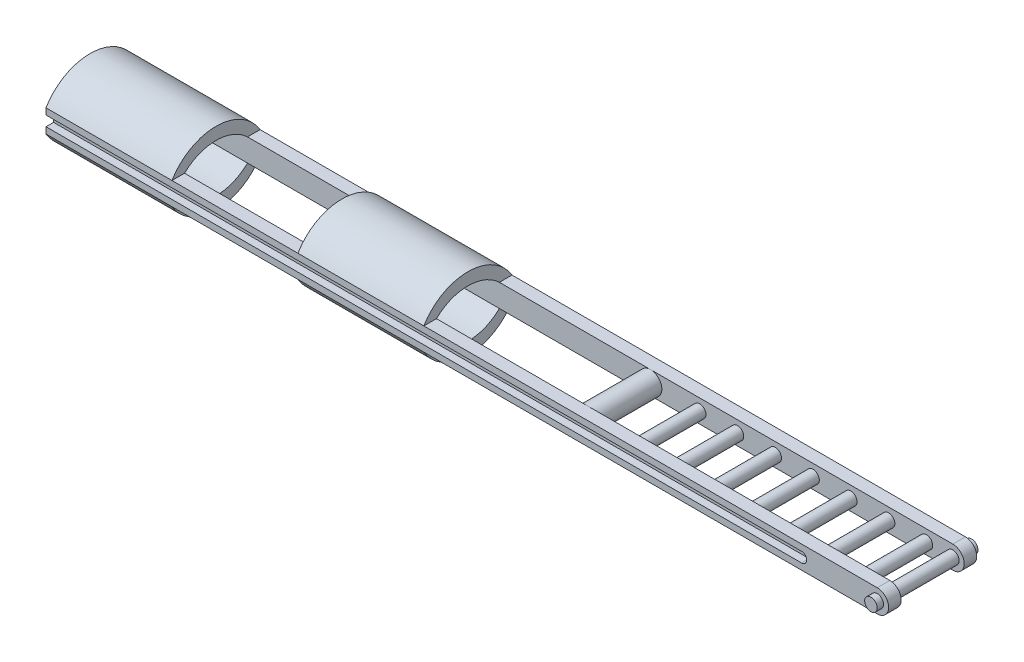
SolidWorks part; units mm, degrees
material "6061-T6 (SS)"
ref_plane "Front" through (0, 0, 0) normal (0, 0, 1) x (1, 0, 0)
ref_plane "Top" through (0, 0, 0) normal (0, 1, 0) x (1, 0, 0)
ref_plane "Right" through (0, 0, 0) normal (1, 0, 0) x (0, 0, -1)
sketch "Croquis1" plane through (0, 0, 0) normal (0, 0, 1) x (1, 0, 0)
  circle A0 centre (0, 0) radius 4.5
  dimension "D1" = 9
extrude "Saliente-Extruir1" add sketch "Croquis1" along normal mid plane 25
sketch "Croquis2" plane through (0, 0, 12.5) normal (0, 0, 1) x (1, 0, 0)
  line L0 (0, 4.5) -> (120, 4.5)
  line L1 (0, -4.5) -> (120, -4.5)
  line L2 (0, 0) -> (120, 0) construction
  arc A0 (120, -4.5) -> (120, 4.5) centre (120, 0) ccw
  circle A1 centre (0, 0) radius 4.5
  arc A2 (0, 4.5) -> (0, -4.5) centre (0, 0) ccw
  dimension "D2" = 120
  dimension "D1" = 0
extrude "Saliente-Extruir2" add sketch "Croquis2" along normal blind 5
mirror "Simetría1" about plane through (0, 0, 0) normal (0, 0, 1) of "Saliente-Extruir2"
sketch "Croquis4" plane through (0, 0, 0) normal (0, 0, 1) x (1, 0, 0)
  circle A0 centre (120, 0) radius 2.5
  arc A2 (120, -4.5) -> (120, 4.5) centre (120, 0) ccw construction
  dimension "D1" = 5
extrude "Saliente-Extruir3" add sketch "Croquis4" along normal mid plane 40
sketch "Croquis5" plane through (0, 0, 17.5) normal (0, 0, 1) x (1, 0, 0)
  line L0 (0, 2) -> (90, 2)
  line L2 (90, -2) -> (0, -2)
  arc A0 (0, 2) -> (0, -2) centre (0, 0) ccw
  arc A1 (90, -2) -> (90, 2) centre (90, 0) ccw
  dimension "D1" = 4
  dimension "D2" = 90
extrude "Cortar-Extruir1" cut sketch "Croquis5" against normal blind 3
mirror "Simetría2" about plane through (0, 0, 0) normal (0, 0, 1) of "Cortar-Extruir1"
sketch "Croquis6" plane through (0, 0, -17.5) normal (0, 0, -1) x (-1, 0, 0)
  line L0 (0, 4.5) -> (210, 4.5)
  line L1 (210, 4.5) -> (210, -4.5)
  line L2 (210, -4.5) -> (0, -4.5)
  arc A0 (0, -4.5) -> (0, 4.5) centre (0, 0) ccw construction
  arc A1 (0, -4.5) -> (0, 4.5) centre (0, 0) ccw
  dimension "D1" = 210
extrude "Saliente-Extruir4" add sketch "Croquis6" against normal up to surface (5 mm away) up to face at (117.5, 0, -12.5)
sketch "Croquis7" plane through (0, 0, -14.5) normal (0, 0, -1) x (-1, 0, 0)
  line L0 (0, 2) -> (256.9255, 2)
  line L1 (256.9255, 2) -> (256.9255, -2)
  line L2 (256.9255, -2) -> (0, -2)
  line L3 (0, 2) -> (0, -2)
extrude "Cortar-Extruir2" cut sketch "Croquis7" along normal blind 10
sketch "Croquis8" plane through (0, 0, 17.5) normal (0, 0, 1) x (1, 0, 0)
  line L0 (0, 4.5) -> (-210, 4.5)
  line L1 (-210, 4.5) -> (-210, -4.5)
  line L2 (-210, -4.5) -> (0, -4.5)
  arc A1 (0, 4.5) -> (0, -4.5) centre (0, 0) ccw construction
  arc A2 (0, 4.5) -> (0, -4.5) centre (0, 0) ccw
extrude "Saliente-Extruir6" add sketch "Croquis8" against normal up to surface (5 mm away) up to face at (122.5, 0, 12.5)
sketch "Croquis9" plane through (0, 0, 14.5) normal (0, 0, 1) x (1, 0, 0)
  line L0 (0, 2) -> (-256.9979, 2)
  line L1 (-256.9979, 2) -> (-256.9979, -2)
  line L2 (-256.9979, -2) -> (0, -2)
  line L3 (0, -2) -> (90, -2) construction
  line L4 (0, -2) -> (0, 2)
  arc A0 (0, 2) -> (0, -2) centre (0, 0) ccw construction
extrude "Cortar-Extruir3" cut sketch "Croquis9" along normal blind 10
sketch "Croquis10" plane through (0, 0, -12.5) normal (0, 0, 1) x (1, 0, 0)
  line L0 (124.5, 0) -> (0, 0) construction
  circle A0 centre (109.5, 0) radius 2.5
  circle A1 centre (120, 0) radius 2.5 construction
  arc A2 (120, -4.5) -> (120, 4.5) centre (120, 0) ccw construction
  circle A3 centre (94.5, 0) radius 2.5
  circle A4 centre (79.5, 0) radius 2.5
  circle A5 centre (64.5, 0) radius 2.5
  circle A6 centre (49.5, 0) radius 2.5
  circle A7 centre (34.5, 0) radius 2.5
  circle A8 centre (19.5, 0) radius 2.5
  dimension "D1" = 15
  dimension "D2" = 7
extrude "Saliente-Extruir7" add sketch "Croquis10" along normal up to surface (25 mm away) up to face at (122.5, 0, 12.5)
sketch "Croquis13" plane through (-210, 0, 0) normal (-1, 0, 0) x (0, 0, 1)
  line L8 (-14.5, 2) -> (-14.5, -2)
  line L9 (-14.5, -2) -> (-17.5, -2)
  line L10 (-17.5, -2) -> (-17.5, -4.5)
  line L11 (-17.5, -4.5) -> (-12.5, -4.5)
  line L12 (-12.5, -4.5) -> (-12.5, 4.5)
  line L13 (-12.5, 4.5) -> (-17.5, 4.5)
  line L14 (-17.5, 4.5) -> (-17.5, 2)
  line L15 (-17.5, 2) -> (-14.5, 2)
  line L18 (-17.5, -2) -> (-17.5, -4.5)
  line L21 (-12.5, 4.5) -> (-17.5, 4.5)
  line L24 (14.5, -2) -> (14.5, 2)
  line L25 (14.5, 2) -> (17.5, 2)
  line L26 (17.5, 2) -> (17.5, 4.5)
  line L27 (17.5, 4.5) -> (12.5, 4.5)
  line L28 (12.5, 4.5) -> (12.5, -4.5)
  line L29 (12.5, -4.5) -> (17.5, -4.5)
  line L30 (17.5, -4.5) -> (17.5, -2)
  line L31 (17.5, -2) -> (14.5, -2)
  line L33 (14.5, 2) -> (17.5, 2)
  line L35 (17.5, 4.5) -> (12.5, 4.5)
  line L38 (17.5, -4.5) -> (17.5, -2)
  arc A0 (-12.5, 4.5) -> (12.5, 4.5) centre (0, -8.488) cw
  arc A1 (17.5, 4.5) -> (-17.5, 4.5) centre (0, -5.988) ccw
  line M24 (-12.5, 4.5) -> (-17.5, 4.5)
  dimension "D1" = 2.5
  dimension "D2" = 0
  dimension "D3" = 0
extrude "Saliente-Extruir9" add sketch "Croquis13" against normal blind 50 contours L35 A1 A0 M24
mirror "Simetría3" about plane through (0, 0, 0) normal (0, 1, 0) of "Saliente-Extruir9"
pattern_linear "MatrizL1" count 2 spacing 100 along (1, 0, 0) of "Simetría3", "Saliente-Extruir9"
